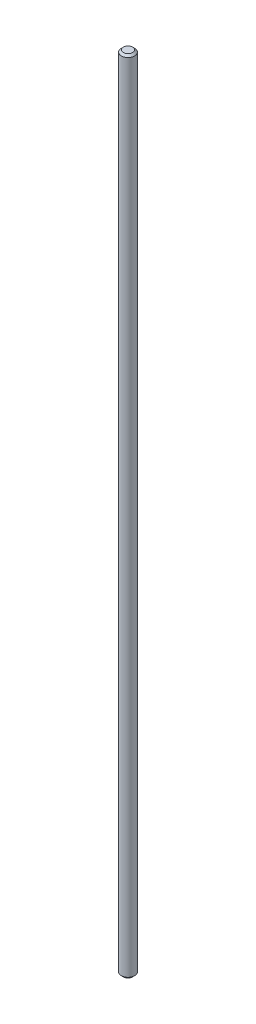
SolidWorks part; units mm, degrees
ref_plane "Front Plane" through (0, 0, 0) normal (0, 0, 1) x (1, 0, 0)
ref_plane "Top Plane" through (0, 0, 0) normal (0, 1, 0) x (1, 0, 0)
ref_plane "Right Plane" through (0, 0, 0) normal (1, 0, 0) x (0, 0, -1)
sketch "Sketch1" plane through (0, 0, 0) normal (0, 1, 0) x (1, 0, 0)
  circle A0 centre (0, 0) radius 2.5
  dimension "D1" = 5
extrude "Boss-Extrude1" add sketch "Sketch1" along normal blind 300
chamfer "Chamfer1" distance 0.75 angle 45 2 edges at (0, 0, 2.5) (0, 300, 2.5)
